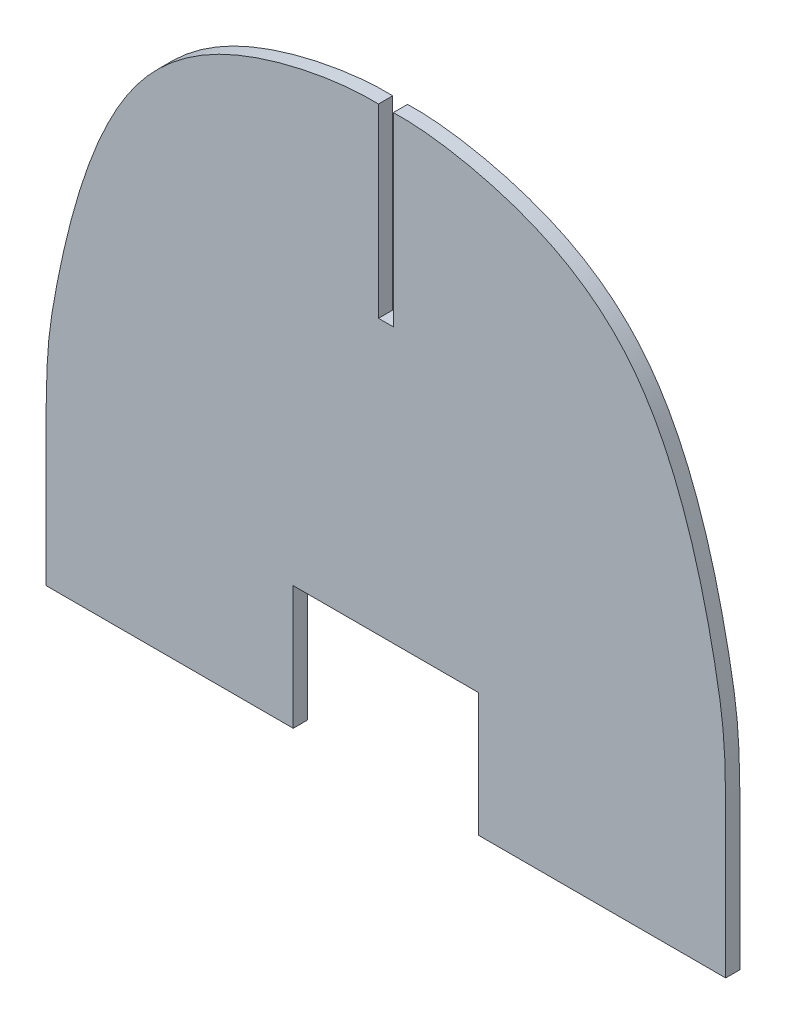
SolidWorks part; units mm, degrees
ref_plane "Front" through (0, 0, 0) normal (0, 0, 1) x (1, 0, 0)
ref_plane "Top" through (0, 0, 0) normal (0, 1, 0) x (1, 0, 0)
ref_plane "Right" through (0, 0, 0) normal (1, 0, 0) x (0, 0, -1)
sketch "Sketch1" plane through (0, 0, 0) normal (0, 0, 1) x (1, 0, 0)
  line L0 (0, 279.4) -> (79.3559, 279.4) construction
  line L1 (139.7, 39.6875) -> (139.7, 138.0054) construction
  spline S0 degree 3 poles (0, 279.4) (0.8995, 279.4) (16.4924, 280.353) (63.3715, 272.2278) (117.0293, 231.6165) (141.432, 126.2334) (139.7, 115.5032) (139.7, 39.6875) knots 0 0 0 0 0.009736 0.194721 0.367315 0.657047 1 1 1 1
sketch "Sketch2" plane through (0, 0, 0) normal (0, 0, 1) x (1, 0, 0)
  line L0 (139.7, 39.6875) -> (0, 39.6875)
  line L1 (0, 39.6875) -> (0, 279.4)
  spline S0 degree 3 poles (-3694.9043, 1809.5161) (-24.7493, 265.967) (-18.9725, 286.4999) (63.3715, 272.2278) (117.0293, 231.6165) (169.6673, 4.2989) (89.2599, 240.1995) (302.4962, -3956.7369) knots -0.27788 -0.27788 -0.27788 -0.27788 0.009736 0.194721 0.367315 0.657047 1.931756 1.931756 1.931756 1.931756 only from (0, 279.4) to (139.7, 39.6875) construction
  spline S1 degree 3 poles (0, 279.4) (0.8995, 279.4) (16.4924, 280.353) (63.3715, 272.2278) (117.0293, 231.6165) (141.432, 126.2334) (139.7, 115.5032) (139.7, 39.6875) knots 0 0 0 0 0.009736 0.194721 0.367315 0.657047 1 1 1 1
extrude "Boss-Extrude1" add sketch "Sketch2" along normal blind 5.842
sketch "Sketch3" plane through (0, 0, 5.842) normal (0, 0, 1) x (1, 0, 0)
  line L0 (0, 279.4) -> (0, 282.2325)
  line L1 (0, 39.6875) -> (38.1, 39.6875)
  line L2 (0, 39.6875) -> (0, 90.4875)
  line L3 (0, 90.4875) -> (38.1, 90.4875)
  line L4 (38.1, 39.6875) -> (38.1, 90.4875)
  line L6 (0, 279.4) -> (0, 203.2)
  line L7 (0, 203.2) -> (3.048, 203.2)
  line L8 (3.048, 282.2325) -> (3.048, 203.2)
  line L9 (0, 282.2325) -> (3.048, 282.2325)
  dimension "D1" = 38.1
  dimension "D2" = 50.8
  dimension "D3" = 76.2
  dimension "D4" = 3.048
extrude "Cut-Extrude1" cut sketch "Sketch3" against normal through all
mirror "Mirror1" about plane through (0, 0, 0) normal (1, 0, 0) of bodies 102
